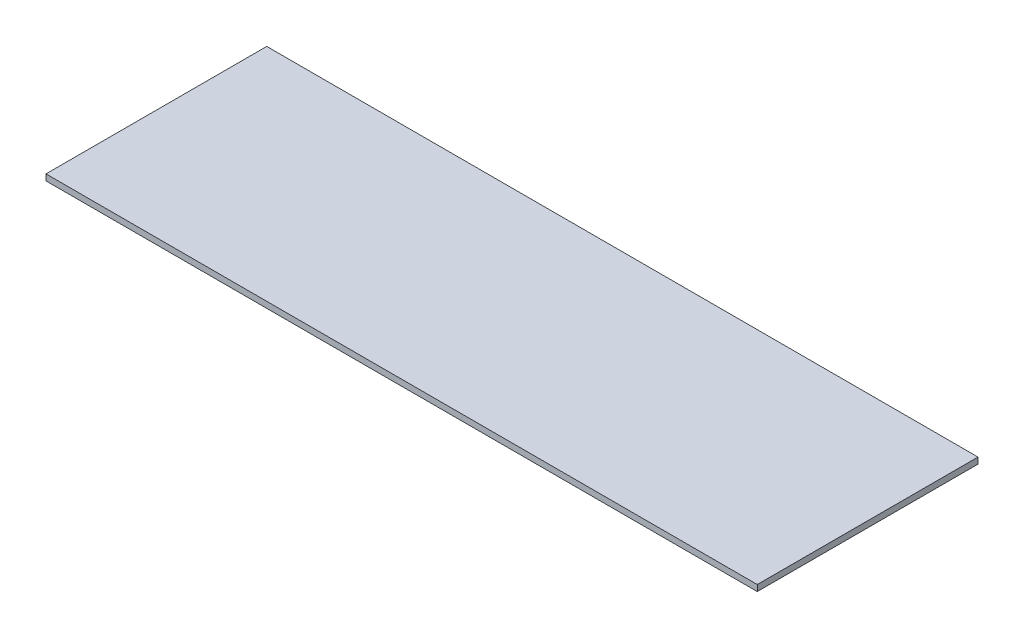
SolidWorks part; units mm, degrees
material "Полиуретановый гибкий пенопласт"
ref_plane "Спереди" through (0, 0, 0) normal (0, 0, 1) x (1, 0, 0)
ref_plane "Сверху" through (0, 0, 0) normal (0, 1, 0) x (1, 0, 0)
ref_plane "Справа" through (0, 0, 0) normal (1, 0, 0) x (0, 0, -1)
sketch "Эскиз1" plane through (0, 0, 0) normal (0, 1, 0) x (1, 0, 0)
  line L1 (0, 0) -> (580, 0)
  line L2 (0, 0) -> (0, 180)
  line L3 (0, 180) -> (580, 180)
  line L4 (580, 0) -> (580, 180)
  dimension "D1" = 580
  dimension "D2" = 180
extrude "Бобышка-Вытянуть1" add sketch "Эскиз1" along normal blind 5
